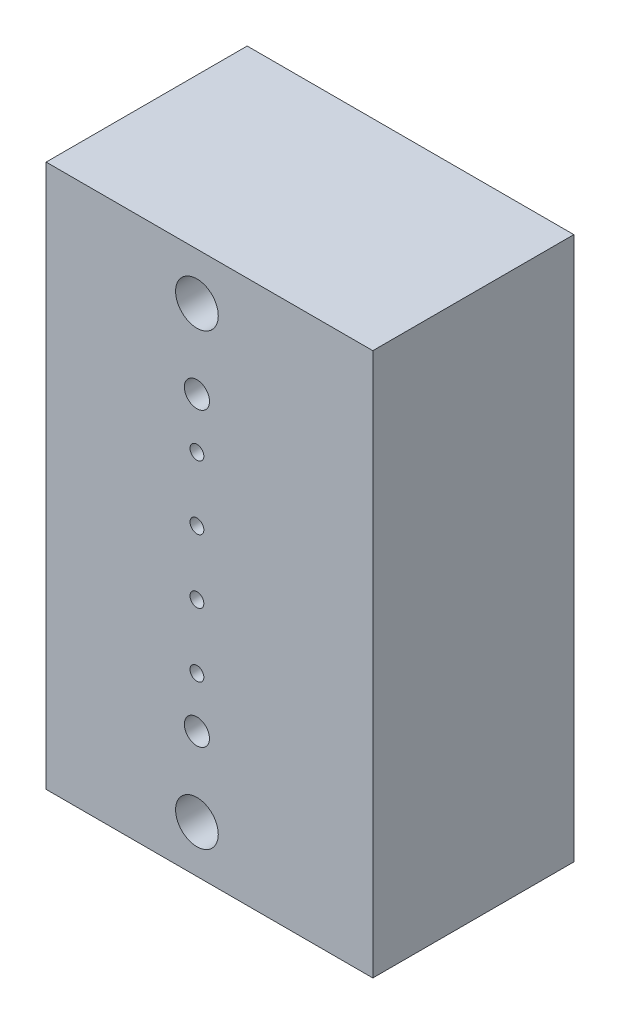
SolidWorks part; units mm, degrees
material "ABS"
ref_plane "Front Plane" through (0, 0, 0) normal (0, 0, 1) x (1, 0, 0)
ref_plane "Top Plane" through (0, 0, 0) normal (0, 1, 0) x (1, 0, 0)
ref_plane "Right Plane" through (0, 0, 0) normal (1, 0, 0) x (0, 0, -1)
sketch "Sketch1" plane through (0, 0, 0) normal (0, 0, 1) x (1, 0, 0)
  line L0 (-4, -16.62) -> (22, -16.62)
  line L1 (22, -16.62) -> (22, 26.62)
  line L2 (22, 26.62) -> (-4, 26.62)
  line L3 (-4, 26.62) -> (-4, -16.62)
  dimension "D1" = 26
  dimension "D2" = 43.24
extrude "Boss-Extrude1" add sketch "Sketch1" along normal blind 16
sketch "Sketch2" plane through (0, 0, 0) normal (0, 0, 1) x (1, 0, 0)
  line L0 (-4, -16.62) -> (22, -16.62) construction
  line L1 (22, -16.62) -> (22, 26.62) construction
  line L2 (22, 26.62) -> (-4, 26.62) construction
  line L3 (-4, 26.62) -> (-4, -16.62) construction
  circle A0 centre (8, -2.62) radius 0.55
  circle A1 centre (8, 2.46) radius 0.55
  circle A2 centre (8, 7.54) radius 0.55
  circle A3 centre (8, 12.62) radius 0.55
  circle A4 centre (8, -12.87) radius 1.7
  circle A5 centre (8, 22.87) radius 1.7
  dimension "D5" = 1.1
  dimension "D6" = 3.4
  dimension "D1" = 12
  dimension "D2" = 14
  dimension "D3" = 5.08
  dimension "D4" = 3.75
extrude "Cut-Extrude1" cut sketch "Sketch2" against normal through all and the other way through all
sketch "Sketch3" plane through (0, 0, 0) normal (0, 0, 1) x (1, 0, 0)
  line L0 (-4, -5.12) -> (10.5, -5.12)
  line L1 (10.5, -5.12) -> (10.5, 15.12)
  line L2 (10.5, 15.12) -> (-4, 15.12)
  line L3 (-4, 15.12) -> (-4, -5.12)
  line L4 (-4, -16.62) -> (22, -16.62) construction
  dimension "D1" = 14.5
  dimension "D2" = 20.24
  dimension "D3" = 11.5
extrude "Cut-Extrude3" cut sketch "Sketch3" along normal blind 4
ref_plane "Plane1" through (0, 0, 16) normal (0, 0, 1) x (1, 0, 0)
sketch "Sketch4" plane through (0, 0, 16) normal (0, 0, 1) x (1, 0, 0)
  line L0 (-4, -16.62) -> (-4, 26.62) construction
  line L1 (-4, -16.62) -> (22, -16.62) construction
  circle A0 centre (8, -6.62) radius 1
  circle A1 centre (8, 16.62) radius 1
  dimension "D1" = 2
  dimension "D2" = 12
  dimension "D3" = 10
  dimension "D4" = 23.24
extrude "Cut-Extrude5" cut sketch "Sketch4" against normal blind 10
